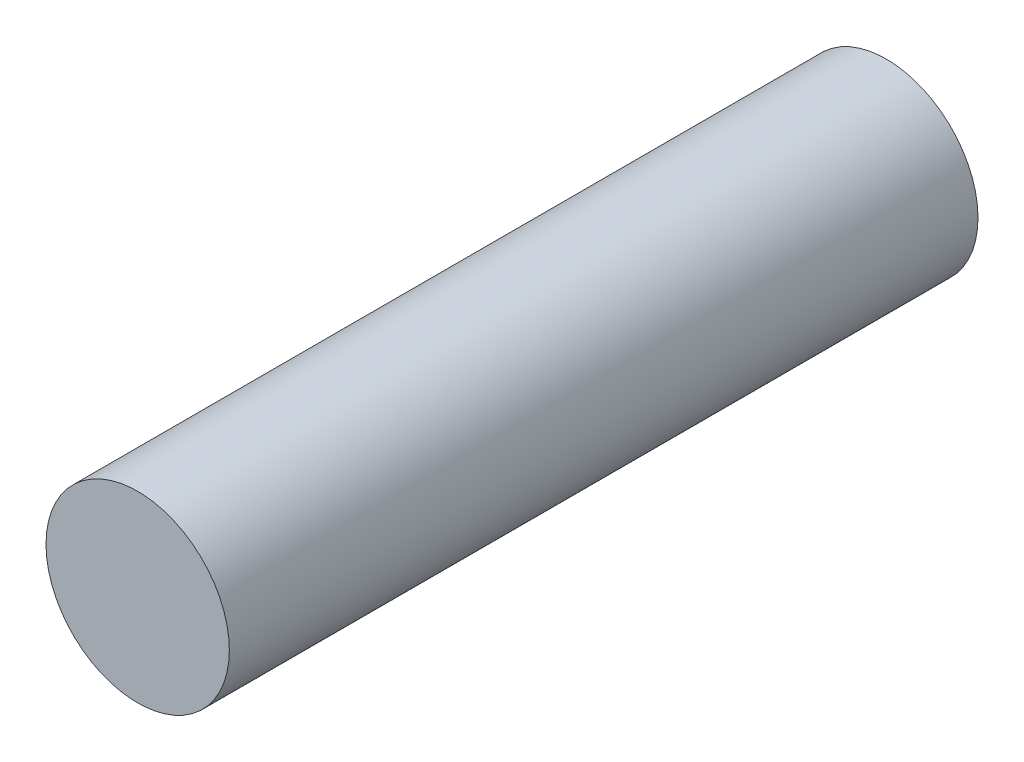
SolidWorks part; units mm, degrees
ref_plane "Plan de face" through (0, 0, 0) normal (0, 0, 1) x (1, 0, 0)
ref_plane "Plan de dessus" through (0, 0, 0) normal (0, 1, 0) x (1, 0, 0)
ref_plane "Plan de droite" through (0, 0, 0) normal (1, 0, 0) x (0, 0, -1)
sketch "Esquisse1" plane through (0, 0, 0) normal (0, 0, 1) x (1, 0, 0)
  circle A0 centre (0, 0) radius 3.11
extrude "Extrusion1" add sketch "Esquisse1" along normal blind 25.4
